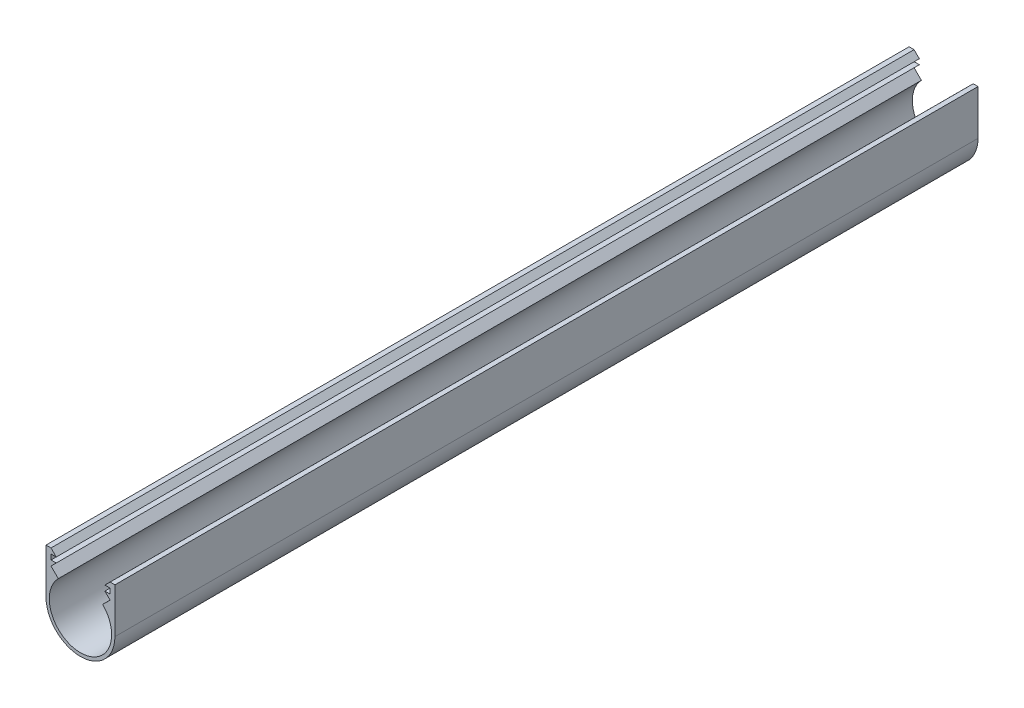
SolidWorks part; units mm, degrees
material "PET"
ref_plane "Front Plane" through (0, 0, 0) normal (0, 0, 1) x (1, 0, 0)
ref_plane "Top Plane" through (0, 0, 0) normal (0, 1, 0) x (1, 0, 0)
ref_plane "Right Plane" through (0, 0, 0) normal (1, 0, 0) x (0, 0, -1)
sketch "Sketch1" plane through (0, 0, 0) normal (0, 0, 1) x (1, 0, 0)
  line L0 (0, 10.5) -> (-11.9582, 10.5)
  line L1 (0, 10.5) -> (18.9213, 10.5)
  line L2 (-10.5, 0) -> (-10.5, 10.5)
  line L3 (10.5, 0) -> (10.5, 10.5)
  circle A0 centre (0, 0) radius 9.5
  circle A1 centre (0, 0) radius 10.5
  dimension "D1" = 19
  dimension "D2" = 21
extrude "Boss-Extrude1" add sketch "Sketch1" along normal blind 263 contours A1 L0 L2 | A1 L3 L1 | A1 A0
sketch "Sketch2" plane through (0, 0, 263) normal (0, 0, 1) x (1, 0, 0)
  line L0 (-10.5, 0) -> (-10.5, 10.5) construction
  line L1 (-10.5, 10.5) -> (-8.976, 10.5)
  line L2 (-10.5, 10.5) -> (-10.5, 13.675)
  line L3 (-10.5, 13.675) -> (-8.976, 13.675)
  line L4 (-8.976, 10.5) -> (-8.976, 13.675)
  line L5 (10.5, 10.5) -> (9.0326, 10.5)
  line L6 (10.5, 10.5) -> (10.5, 13.675)
  line L7 (10.5, 13.675) -> (9.0326, 13.675)
  line L8 (9.0326, 10.5) -> (9.0326, 13.675)
  line L9 (-7.3758, 12.0748) -> (-8.976, 13.675)
  line L10 (-8.976, 13.675) -> (-7.3758, 13.675)
  line L11 (-8.976, 13.675) -> (-8.976, 12.0748)
  line L12 (-8.976, 12.0748) -> (-7.3758, 12.0748)
  line L13 (-7.3758, 13.675) -> (-7.3758, 12.0748)
  line L14 (-7.3758, 12.0748) -> (9.0326, 12.0875)
  line L15 (9.0326, 13.675) -> (7.4324, 12.0863)
  line M10 (10.5, 10.5) -> (-10.5, 10.5)
  dimension "D1" = 18.0086
  dimension "D2" = 21
  dimension "D3" = 1.524
  dimension "D4" = 1.4674
  dimension "D5" = 3.175
  dimension "D6" = 0
  dimension "D7" = 1.5748
  dimension "D8" = 1.6002
  dimension "D9" = 1.6002
  dimension "D10" = 1.6002
extrude "Boss-Extrude2" add sketch "Sketch2" against normal up to surface (263 mm away) contours L4 L3 L2 M10 | L4 L12 L9 | L8 L15 L14 | L8 L6 L7 M10 up to face at (0, 2.625, 0)
sketch "Sketch3" plane through (0, 0, 263) normal (0, 0, 1) x (1, 0, 0)
  line L0 (9.0326, 8.8998) -> (7.4324, 10.5)
  line L1 (9.0326, 10.5) -> (-8.976, 10.5)
  line L2 (9.0326, 10.5) -> (9.0326, 8.8998)
  line L3 (9.0326, 8.8998) -> (-8.976, 8.8998)
  line L4 (-8.976, 10.5) -> (-8.976, 8.8998)
  line L5 (7.4324, 10.5) -> (9.0326, 10.5)
  line L6 (-7.3758, 12.0748) -> (-7.3758, 10.5)
  line L7 (-7.3758, 10.5) -> (-8.976, 8.8998)
  line L8 (9.0326, 8.8998) -> (6.7671, 6.6676)
  line L9 (-8.976, 8.8998) -> (-6.7461, 6.6888)
  circle A0 centre (0, 0) radius 9.5 construction
  line M9 (9.0326, 10.5) -> (-8.976, 10.5)
  circle M14 centre (0, 0) radius 9.5
  dimension "D1" = 0
  dimension "D2" = 1.6002
  dimension "D3" = 0
extrude "Cut-Extrude1" cut sketch "Sketch3" against normal through all contours L3 L9 M14 | L7 L3 L0 M9 M14 | L8 L3 M14
